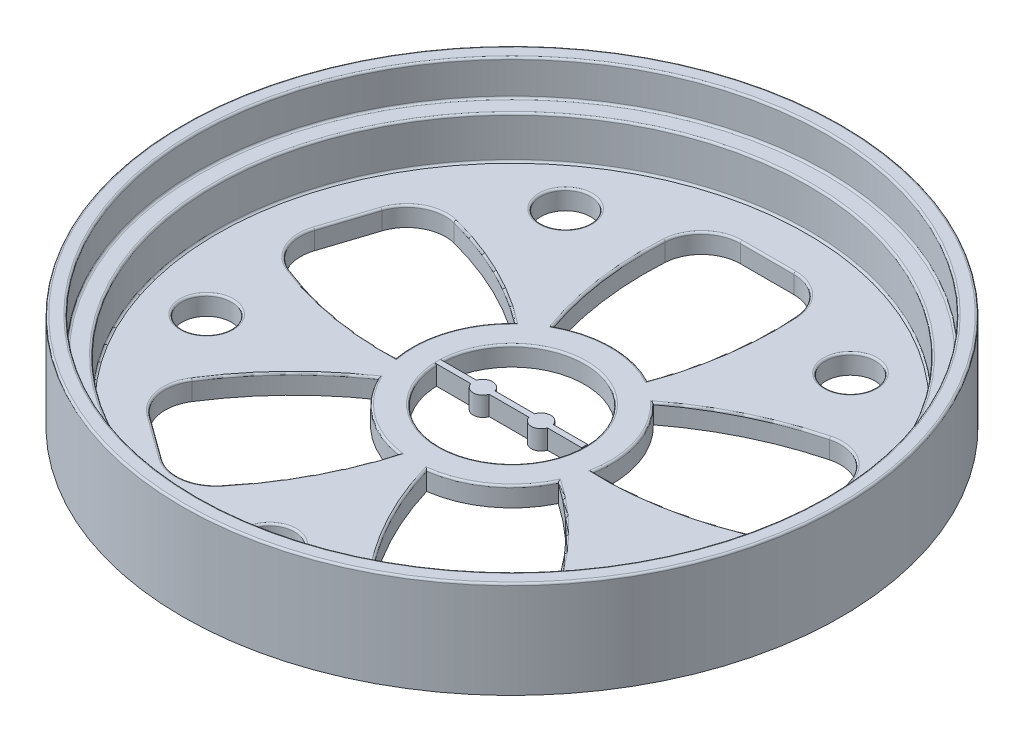
SolidWorks part; units mm, degrees
material "ABS"
ref_plane "Front Plane" through (0, 0, 0) normal (0, 0, 1) x (1, 0, 0)
ref_plane "Top Plane" through (0, 0, 0) normal (0, 1, 0) x (1, 0, 0)
ref_plane "Right Plane" through (0, 0, 0) normal (1, 0, 0) x (0, 0, -1)
sketch "Sketch1" plane through (0, 0, 0) normal (0, 1, 0) x (1, 0, 0)
  line L0 (0, 0) -> (0, 9.525) construction
  line L1 (0, 0) -> (0, -9.525) construction
  line L2 (0, 0) -> (9.525, 0) construction
  line L3 (0, 0) -> (-9.525, 0) construction
  line L4 (-3.5014, 33.4208) -> (3.5014, 33.4208)
  line L5 (30.7031, 13.6576) -> (32.8671, 6.9976)
  line L6 (22.477, -24.9799) -> (16.8116, -29.0961)
  line L7 (-16.8116, -29.0961) -> (-22.477, -24.9799)
  line L8 (-32.8671, 6.9976) -> (-30.7031, 13.6576)
  circle A0 centre (0, 0) radius 43.18
  circle A1 centre (18.6622, 25.6863) radius 3.2512
  circle A2 centre (30.196, -9.8113) radius 3.2512
  circle A3 centre (0, -31.75) radius 3.2512
  circle A4 centre (-30.196, -9.8113) radius 3.2512
  circle A5 centre (-18.6622, 25.6863) radius 3.2512
  circle A6 centre (0, 0) radius 9.525
  arc A7 (6.1724, 11.5512) -> (-6.1724, 11.5512) centre (0, 0) ccw
  arc A8 (6.1724, 11.5512) -> (8.5721, 28.6483) centre (-34.7966, 26.0184) ccw
  arc A9 (8.5721, 28.6483) -> (3.5014, 33.4208) centre (3.5014, 28.3408) ccw
  arc A10 (-3.5014, 33.4208) -> (-8.5721, 28.6483) centre (-3.5014, 28.3408) ccw
  arc A11 (-8.5721, 28.6483) -> (-6.1724, 11.5512) centre (34.7966, 26.0184) ccw
  arc A12 (24.5972, 17.0054) -> (9.0784, 9.4398) centre (35.4977, -25.0534) ccw
  arc A13 (30.7031, 13.6576) -> (24.5972, 17.0054) centre (25.8717, 12.0878) ccw
  arc A14 (29.8951, 0.7003) -> (32.8671, 6.9976) centre (28.0357, 5.4277) ccw
  arc A15 (12.8932, -2.3008) -> (29.8951, 0.7003) centre (13.9922, 41.1336) ccw
  arc A16 (12.8932, -2.3008) -> (9.0784, 9.4398) centre (0, 0) ccw
  arc A17 (1.796, -12.9731) -> (11.7832, -5.717) centre (0, 0) ccw
  arc A18 (23.774, -18.1384) -> (11.7832, -5.717) centre (-12.8578, -41.5022) ccw
  arc A19 (22.477, -24.9799) -> (23.774, -18.1384) centre (19.491, -20.8701) ccw
  arc A20 (9.9041, -28.2155) -> (16.8116, -29.0961) centre (13.8256, -24.9863) ccw
  arc A21 (1.796, -12.9731) -> (9.9041, -28.2155) centre (43.4442, -0.5964) ccw
  arc A22 (-11.7832, -5.717) -> (-1.796, -12.9731) centre (0, 0) ccw
  arc A23 (-9.9041, -28.2155) -> (-1.796, -12.9731) centre (-43.4442, -0.5964) ccw
  arc A24 (-16.8116, -29.0961) -> (-9.9041, -28.2155) centre (-13.8256, -24.9863) ccw
  arc A25 (-23.774, -18.1384) -> (-22.477, -24.9799) centre (-19.491, -20.8701) ccw
  arc A26 (-11.7832, -5.717) -> (-23.774, -18.1384) centre (12.8578, -41.5022) ccw
  arc A27 (-9.0784, 9.4398) -> (-12.8932, -2.3008) centre (0, 0) ccw
  arc A28 (-29.8951, 0.7003) -> (-12.8932, -2.3008) centre (-13.9922, 41.1336) ccw
  arc A29 (-32.8671, 6.9976) -> (-29.8951, 0.7003) centre (-28.0357, 5.4277) ccw
  arc A30 (-24.5972, 17.0054) -> (-30.7031, 13.6576) centre (-25.8717, 12.0878) ccw
  arc A31 (-9.0784, 9.4398) -> (-24.5972, 17.0054) centre (-35.4977, -25.0534) ccw
  dimension "D1" = 86.36
extrude "Yükseklik-Ekstrüzyon1" add sketch "Sketch1" along normal blind 2.54 contours A0 A31 A27 A28 A29 L8 A30 A26 A22 A23 A24 L7 A25 A21 A17 A18 A19 L6 A20 A11 A10 L4 A9 A8 A7 A6 A5 A4 A3 A2 A1 A15 A16 A12 A13 L5 A14
sketch "Çizim1" plane through (0, 2.54, 0) normal (0, 1, 0) x (1, 0, 0)
  circle A0 centre (0, 0) radius 43.18 construction
  circle A1 centre (0, 0) radius 43.18
  circle A2 centre (0, 0) radius 38.8938
  dimension "D1" = 77.7875
extrude "Yükseklik-Ekstrüzyon2" add sketch "Çizim1" along normal blind 10.16
sketch "Çizim2" plane through (0, 12.7, 0) normal (0, 1, 0) x (1, 0, 0)
  circle A0 centre (0, 0) radius 41.275
  dimension "D1" = 82.55
extrude "Kes-Ekstrüzyon2" cut sketch "Çizim2" against normal blind 4.6355
fillet "Radyus1" radius 0.254 41 edges at (0, 12.7, 43.18) (0, 12.7, 41.275) (0, 8.0645, 41.275) (0, 8.0645, 38.8938) (0, 2.54, 38.8938) (-28.314, 2.54, -16.5422) (-31.7851, 2.54, -10.3276) (-32.6298, 2.54, -3.2596) (-21.5447, 2.54, 1.6533) (-12.4559, 2.54, -4.0472) (-16.4583, 2.54, -14.0012) (-24.4821, 2.54, 21.8164) (-19.6443, 2.54, 27.038) (-13.1832, 2.54, 30.0255) (-5.0853, 2.54, 21.0011) (-7.6981, 2.54, 10.5956) (-18.4018, 2.54, 11.3261) (13.1832, 2.54, 30.0255) (19.6443, 2.54, 27.038) (24.4821, 2.54, 21.8164) (18.4018, 2.54, 11.3261) (7.6981, 2.54, 10.5956) (5.0853, 2.54, 21.0011) (0, 2.54, -13.0969) (8.23, 2.54, -19.9793) (6.9831, 2.54, -32.04) (0, 2.54, -33.4208) (-6.9831, 2.54, -32.04) (-8.23, 2.54, -19.9793) (0, 2.54, 9.525) (-18.6622, 2.54, -22.4351) (-30.196, 2.54, 13.0625) (0, 2.54, 35.0012) (30.196, 2.54, 13.0625) (18.6622, 2.54, -22.4351) (32.6298, 2.54, -3.2596) (31.7851, 2.54, -10.3276) (28.314, 2.54, -16.5422) (16.4583, 2.54, -14.0012) (12.4559, 2.54, -4.0472) (21.5447, 2.54, 1.6533)
sketch "Çizim3" plane through (0, 2.54, 0) normal (0, 1, 0) x (1, 0, 0)
  line L1 (-9.7711, -0.387) -> (-5.0196, -0.387)
  line L2 (-9.7711, -0.387) -> (-9.7711, 0.375)
  line L3 (-9.7711, 0.375) -> (-5.0234, 0.375)
  line L4 (9.5176, -0.387) -> (9.5176, 0.375)
  line L8 (5.0196, -0.387) -> (9.5176, -0.387)
  line L9 (5.0234, 0.375) -> (9.5176, 0.375)
  line L10 (-2.6004, -0.387) -> (2.6004, -0.387)
  line L13 (-2.5966, 0.375) -> (2.5966, 0.375)
  arc A1 (5.0234, 0.375) -> (2.5966, 0.375) centre (3.81, 0) ccw
  arc A2 (-2.5966, 0.375) -> (-5.0234, 0.375) centre (-3.81, 0) ccw
  circle A3 centre (0, 0) radius 9.525 construction
  arc A4 (2.6004, -0.387) -> (5.0196, -0.387) centre (3.81, 0) ccw
  arc A5 (-5.0196, -0.387) -> (-2.6004, -0.387) centre (-3.81, 0) ccw
  point P4 (0, 0)
  dimension "D1" = 2.54
  dimension "D2" = 2.54
  dimension "D3" = 3.81
  dimension "D4" = 3.81
  dimension "D5" = 0.762
extrude "Yükseklik-Ekstrüzyon3" add sketch "Çizim3" against normal up to surface (2.54 mm away) separate body contours L8 L4 L9 A1 L13 A2 L3 L2 L1 A5 L10 A4 up to face at (-23.8646, 0, -7.7541)
